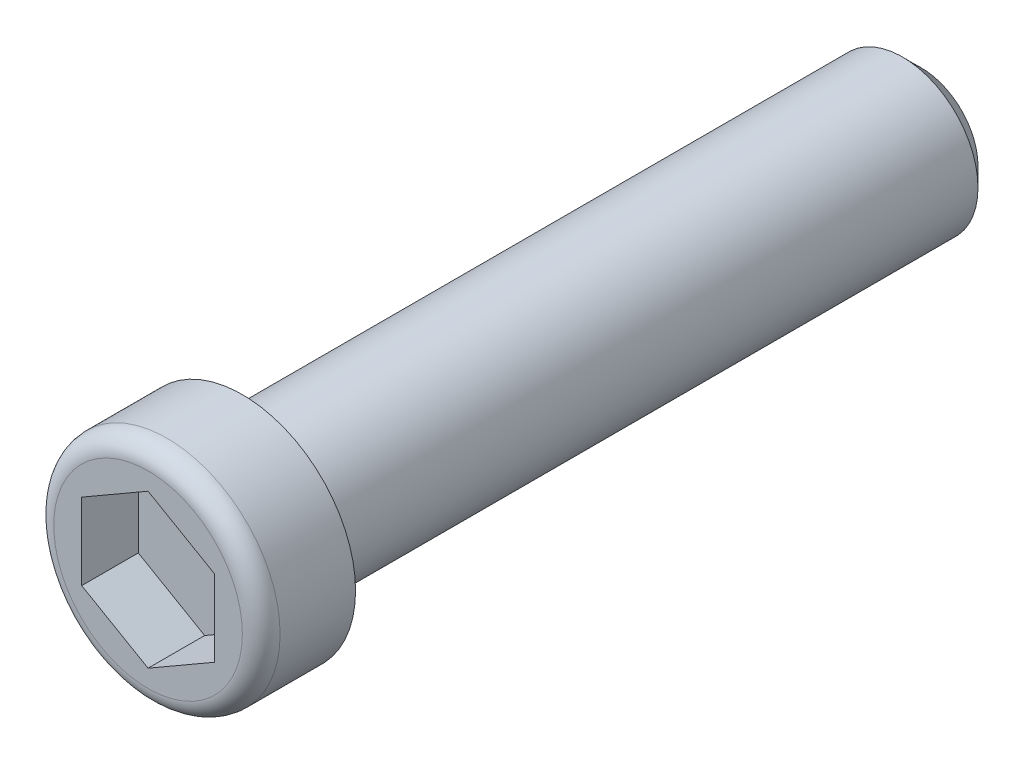
SolidWorks part; units mm, degrees
ref_plane "前视基准面" through (0, 0, 0) normal (0, 0, 1) x (1, 0, 0)
ref_plane "上视基准面" through (0, 0, 0) normal (0, 1, 0) x (1, 0, 0)
ref_plane "右视基准面" through (0, 0, 0) normal (1, 0, 0) x (0, 0, -1)
sketch "草图1" plane through (0, 0, 0) normal (0, 0, 1) x (1, 0, 0)
  circle A0 centre (0, 0) radius 2
extrude "凸台-拉伸1" add sketch "草图1" along normal blind 18
sketch "草图2" plane through (0, 0, 18) normal (0, 0, 1) x (1, 0, 0)
  circle A0 centre (0, 0) radius 3
extrude "凸台-拉伸2" add sketch "草图2" along normal blind 2.5
sketch "草图4" plane through (0, 0, 20.5) normal (0, 0, 1) x (1, 0, 0)
  line L1 (0, 2.0316) -> (-1.7595, 1.0158)
  line L2 (-1.7595, 1.0158) -> (-1.7595, -1.0158)
  line L3 (-1.7595, -1.0158) -> (0, -2.0316)
  line L4 (0, -2.0316) -> (1.7595, -1.0158)
  line L5 (1.7595, -1.0158) -> (1.7595, 1.0158)
  line L6 (1.7595, 1.0158) -> (0, 2.0316)
  circle A0 centre (0, 0) radius 1.7595 construction
extrude "切除-拉伸1" cut sketch "草图4" against normal blind 1.5
chamfer "倒角1" distance 0.5 angle 45 1 edges at (2, 0, 0)
fillet "圆角1" radius 0.5 1 edges at (3, 0, 20.5)
